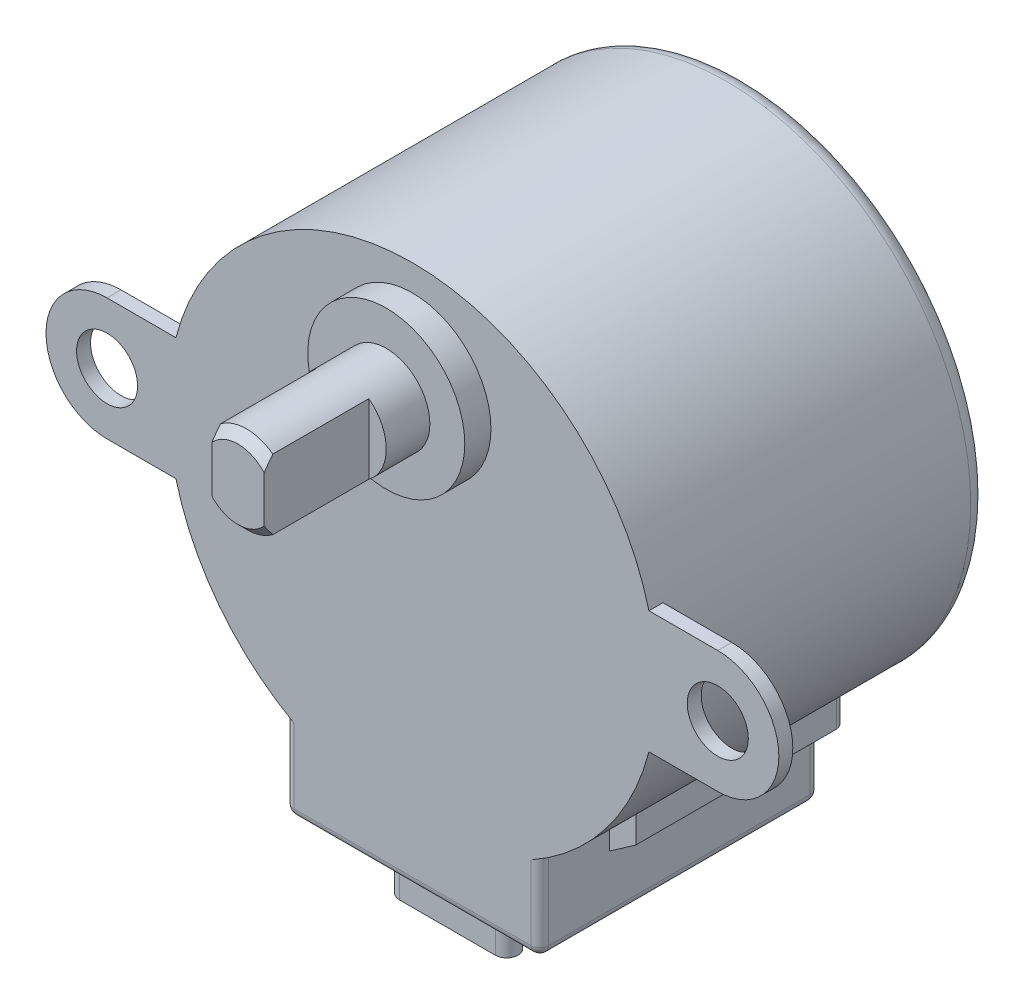
SolidWorks part; units mm, degrees
ref_plane "Plano frontal" through (0, 0, 0) normal (0, 0, 1) x (1, 0, 0)
ref_plane "Plano superior" through (0, 0, 0) normal (0, 1, 0) x (1, 0, 0)
ref_plane "Plano direito" through (0, 0, 0) normal (1, 0, 0) x (0, 0, -1)
sketch "Esboço1" plane through (0, 0, 0) normal (0, 0, 1) x (1, 0, 0)
  circle A0 centre (0, 0) radius 14
  dimension "D1" = 28
extrude "Ressalto-extrusão1" add sketch "Esboço1" along normal blind 19
sketch "Esboço2" plane through (0, 0, 19) normal (0, 0, 1) x (1, 0, 0)
  circle A0 centre (0, 8) radius 4.5
  dimension "D2" = 9
  dimension "D1" = 8
extrude "Ressalto-extrusão2" add sketch "Esboço2" along normal blind 1.5
sketch "Esboço3" plane through (0, 0, 19) normal (0, 0, 1) x (1, 0, 0)
  circle A0 centre (0, 8) radius 2.5
  dimension "D1" = 5
extrude "Ressalto-extrusão3" add sketch "Esboço3" along normal blind 10 contours A0
sketch "Esboço5" plane through (0, 0, 29) normal (0, 0, 1) x (1, 0, 0)
  line L2 (-1.5, 10.5862) -> (-1.5, 5.4138)
  line L4 (1.5, 10.5862) -> (1.5, 5.4138)
  arc A0 (1.5, 5.4138) -> (1.5, 10.5862) centre (0, 8) ccw
  arc A1 (-1.5, 10.5862) -> (-1.5, 5.4138) centre (0, 8) ccw
  point P0 (0, 8)
extrude "Corte-extrusão1" cut sketch "Esboço5" against normal blind 6
chamfer "Chanfro2" distance 0.5 angle 45 2 edges at (0, 5.5, 29) (0, 10.5, 29)
sketch "Esboço6" plane through (0, 0, 19) normal (0, 0, 1) x (1, 0, 0)
  line L0 (-17.5, 0) -> (0, 0) construction
  line L1 (0, 0) -> (17.5, 0) construction
  line L3 (17.5, 3.5) -> (-17.5, 3.5)
  line L5 (17.5, -3.5) -> (-17.5, -3.5)
  circle A0 centre (-17.5, 0) radius 1.75
  circle A1 centre (17.5, 0) radius 1.75
  arc A3 (-17.5, 3.5) -> (-17.5, -3.5) centre (-17.5, 0) ccw
  arc A4 (17.5, -3.5) -> (17.5, 3.5) centre (17.5, 0) ccw
  dimension "D1" = 3.5
  dimension "D2" = 3.5
  dimension "D3" = 35
  dimension "D4" = 17.5
extrude "Ressalto-extrusão5" add sketch "Esboço6" against normal blind 0.8
fillet "Filete1" radius 1 1 edges at (14, 0, 0)
sketch "Esboço7" plane through (0, 0, 19) normal (0, 0, 1) x (1, 0, 0)
  line L3 (7.3, -17) -> (-7.3, -17)
  line L8 (-7.3, -11.9461) -> (-7.3, -17)
  line L9 (7.3, -11.9461) -> (7.3, -17)
  arc A0 (-7.3, -11.9461) -> (7.3, -11.9461) centre (0, 0) ccw
  point P0 (0, 0)
  dimension "D1" = 14.6
  dimension "D2" = 17
extrude "Ressalto-extrusão6" add sketch "Esboço7" against normal blind 16
sketch "Esboço8" plane through (0, 0, 3) normal (0, 0, -1) x (-1, 0, 0)
  line L3 (0, -17) -> (0, -14.4851) construction
  line L4 (7.3, -17) -> (-7.3, -17) construction
  line L9 (-7.3, -13.5559) -> (-8.8, -12.5056)
  line L11 (-7.3, -17) -> (-7.3, -11.9461) construction
  line L12 (-8.8, -12.5056) -> (-8.8, -10.8885)
  line L13 (-7.3, -13.5559) -> (-7.3, -11.9461)
  line L14 (7.3, -13.5559) -> (7.3, -11.9461)
  line L15 (8.8, -12.5056) -> (8.8, -10.8885)
  line L16 (7.3, -13.5559) -> (8.8, -12.5056)
  circle A3 centre (0, 0) radius 14 construction
  arc A4 (-8.8, -10.8885) -> (-7.3, -11.9461) centre (0, 0) ccw
  arc A5 (8.8, -10.8885) -> (7.3, -11.9461) centre (0, 0) cw
  dimension "D1" = 125
  dimension "D2" = 1.5
extrude "Ressalto-extrusão7" add sketch "Esboço8" against normal blind 12
fillet "Filete2" radius 0.5 12 edges at (0, -17, 19) (8.8, -11.6971, 3) (8.05, -13.0308, 3) (7.3, -15.278, 3) (-7.3, -15.278, 3) (-8.05, -13.0308, 3) (-8.8, -11.6971, 3) (0, -17, 3) (-7.3, -17, 11) (7.3, -17, 11) (-7.3, -14.4731, 19) (7.3, -14.4731, 19)
sketch "Esboço9" plane through (0, -17, 0) normal (0, -1, 0) x (1, 0, 0)
  line L0 (-2.75, 16.35) -> (2.75, 16.35) construction
  line L1 (-2.75, 17) -> (2.75, 17)
  line L2 (-2.75, 15.7) -> (2.75, 15.7)
  line L3 (0, 18.5) -> (0, 11.8403) construction
  line L4 (6.8, 18.5) -> (-6.8, 18.5) construction
  arc A0 (-2.75, 17) -> (-2.75, 15.7) centre (-2.75, 16.35) ccw
  arc A1 (2.75, 15.7) -> (2.75, 17) centre (2.75, 16.35) ccw
  point P2 (0, 16.35)
  point P12 (0, 0)
  dimension "D1" = 5.5
  dimension "D2" = 1.3
  dimension "D3" = 1.5
extrude "Ressalto-extrusão8" add sketch "Esboço9" along normal blind 3
